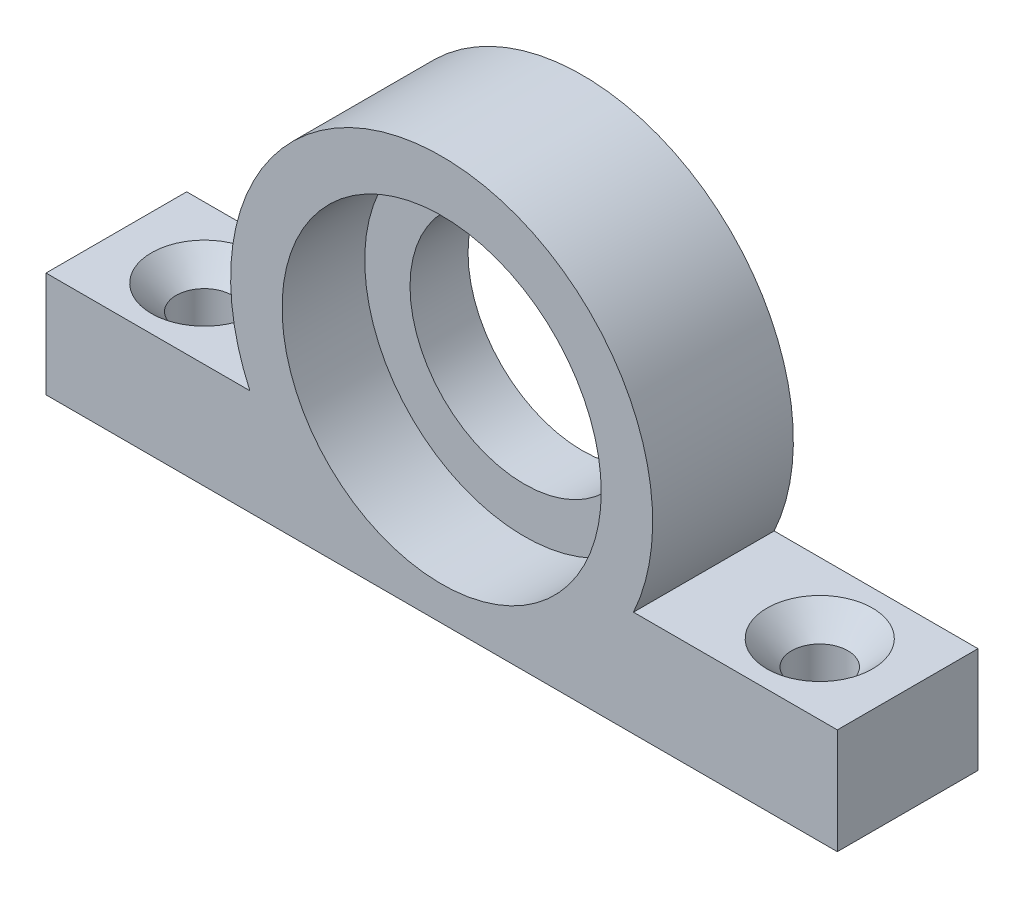
SolidWorks part; units mm, degrees
ref_plane "Front Plane" through (0, 0, 0) normal (0, 0, 1) x (1, 0, 0)
ref_plane "Top Plane" through (0, 0, 0) normal (0, 1, 0) x (1, 0, 0)
ref_plane "Right Plane" through (0, 0, 0) normal (1, 0, 0) x (0, 0, -1)
sketch "Sketch1" plane through (0, 0, 0) normal (0, 0, 1) x (1, 0, 0)
  line L0 (-22.5, 6) -> (-22.5, 11) construction
  line L1 (0, 0) -> (-45, 0)
  line L2 (0, 0) -> (0, 6)
  line L3 (0, 6) -> (-45, 6)
  line L4 (-45, 0) -> (-45, 6)
  circle A0 centre (-22.5, 11) radius 6.5
  circle A1 centre (-22.5, 11) radius 12
  spline S0 degree 2 poles (-36, 6) (-34.1882, 10.9779) (-34.5, 11) knots 0 0 0 1 1 1
  spline S1 degree 2 poles (-9, 6) (-10.8118, 10.9779) (-10.5, 11) knots 0 0 0 1 1 1
  point P5 (-22.5, 6)
  point P10 (-34.5, 11)
  point P11 (-10.5, 11)
  point P12 (-9, 6)
  point P13 (-36, 6)
  dimension "D3" = 13
  dimension "D5" = 24
  dimension "D1" = 6
  dimension "D2" = 45
  dimension "D4" = 5
  dimension "D6" = 9
  dimension "D7" = 9
extrude "Boss-Extrude1" add sketch "Sketch1" along normal blind 8 contours L3 A1 L1 A0 | A1 L3 L4 L1 | A1 S1 S0 L3 A0 | A1 L1 L2 L3 | A1 S0 | S1 A1
sketch "Sketch2" plane through (0, 0, 8) normal (0, 0, 1) x (1, 0, 0)
  circle A0 centre (-22.5, 11) radius 9.075
  circle A1 centre (-22.5, 11) radius 6.5 construction
  dimension "D1" = 18.15
extrude "Cut-Extrude1" cut sketch "Sketch2" against normal blind 4.7
sketch "Sketch3" plane through (0, 6, 0) normal (0, 1, 0) x (1, 0, 0)
  line L0 (-40, 0) -> (-40, -8) construction
  line L1 (-33.4087, 0) -> (-45, 0) construction
  line L2 (-33.4087, -8) -> (-45, -8) construction
  line L3 (-5, 0) -> (-5, -8) construction
  line L4 (0, 0) -> (-11.5913, 0) construction
  line L5 (0, -8) -> (-11.5913, -8) construction
  line L6 (-45, -8) -> (-45, 0) construction
  line L7 (-40, -4) -> (-45, -4) construction
  line L8 (-5, -4) -> (0, -4) construction
  line L9 (0, -8) -> (0, 0) construction
  point P12 (-40, -4)
  point P13 (-5, -4)
  dimension "D1" = 35
hole_wizard "Hole1" positions "3DSketch1" profile "Sketch5" legacy end condition through all
sketch3d "3DSketch1"
  point P0 (-40, 6, 4)
  point P3 (-5, 6, 4)
sketch "Sketch5" plane through (-40, 6, 4) normal (1, 0, 0) x (0, 0, 1)
  line L0 (0, 0) -> (0, 6)
  line L1 (0, 6) -> (1.6, 6)
  line L2 (1.6, 6) -> (1.6, 1.4)
  line L3 (1.6, 1.4) -> (3, 0)
  line L4 (3, 0) -> (0, 0)
  line L5 (0, -6.4453) -> (0, 115.525) construction
  line L6 (-1.6, 1.4) -> (-3, 0) construction
  dimension "Diameter" = 3.2
  dimension "Depth" = 6
  dimension "C-Sink Angle" = 90
  dimension "C-Sink Diameter" = 6
